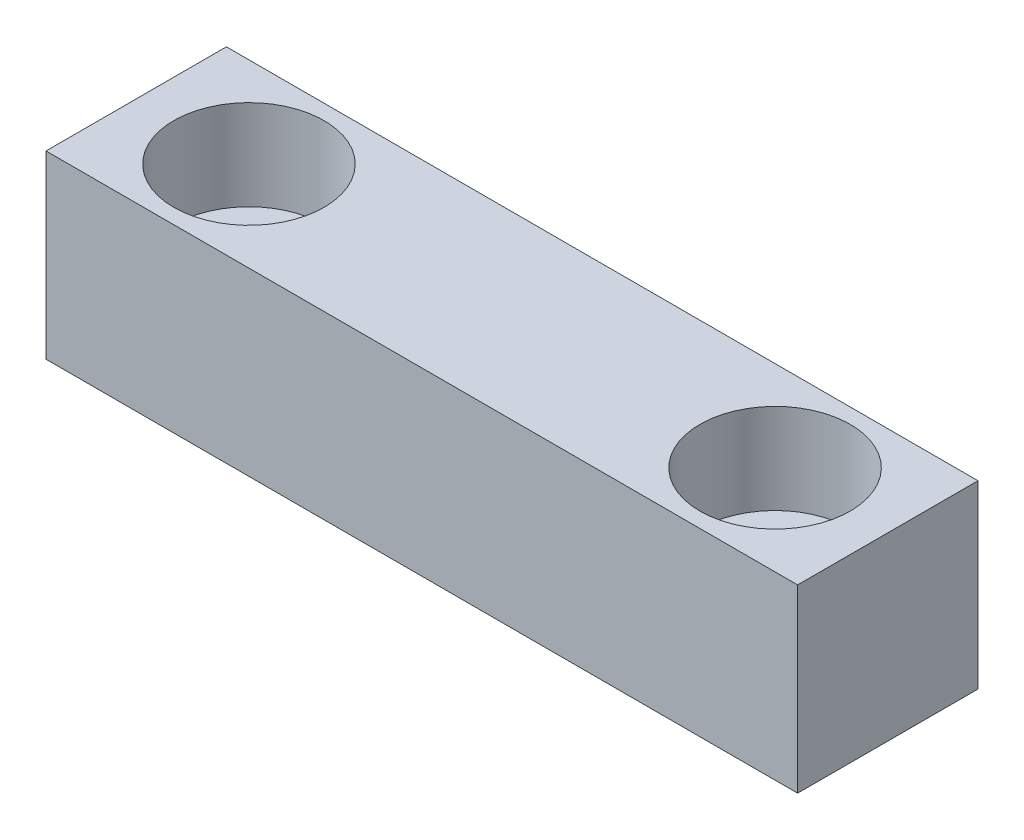
SolidWorks part; units mm, degrees
ref_plane "Front Plane" through (0, 0, 0) normal (0, 0, 1) x (1, 0, 0)
ref_plane "Top Plane" through (0, 0, 0) normal (0, 1, 0) x (1, 0, 0)
ref_plane "Right Plane" through (0, 0, 0) normal (1, 0, 0) x (0, 0, -1)
sketch "Sketch1" plane through (0, 0, 0) normal (0, 1, 0) x (1, 0, 0)
  line L1 (0, 0) -> (50, 0)
  line L2 (0, 0) -> (0, 12)
  line L3 (0, 12) -> (50, 12)
  line L4 (50, 0) -> (50, 12)
  dimension "D1" = 50
  dimension "D2" = 12
extrude "Boss-Extrude1" add sketch "Sketch1" along normal mid plane 12
hole_wizard "CBORE for M5 Hex Socket Head Cap Screw1" positions "Sketch2" profile "Sketch3" counterbore size "M5" standard "ISO" end condition through all
sketch "Sketch2" plane through (0, 6, 0) normal (0, 1, 0) x (1, 0, 0)
  line L0 (50, 12) -> (0, 12) construction
  point P2 (42.5, 6)
  point P4 (7.5, 6)
  point P7 (0, 0)
  point P8 (7.3611, 6)
  point P11 (25, 12)
  dimension "D1" = 17.5
  dimension "D2" = 35
sketch "Sketch3" plane through (42.5, 6, -6) normal (1, 0, 0) x (0, 0, 1)
  line L0 (0, 0) -> (0, 12)
  line L1 (0, 12) -> (2.75, 12)
  line L3 (2.75, 12) -> (2.75, 6)
  line L4 (2.75, 6) -> (5, 6)
  line L5 (5, 6) -> (5, 0)
  line L7 (5, 0) -> (0, 0)
  line L11 (0, -6.35) -> (0, 107.95) construction
  dimension "Thru Hole Dia." = 5.5
  dimension "Thru Hole Depth" = 12
  dimension "C'Bore Dia." = 10
  dimension "C'Bore Depth" = 6
